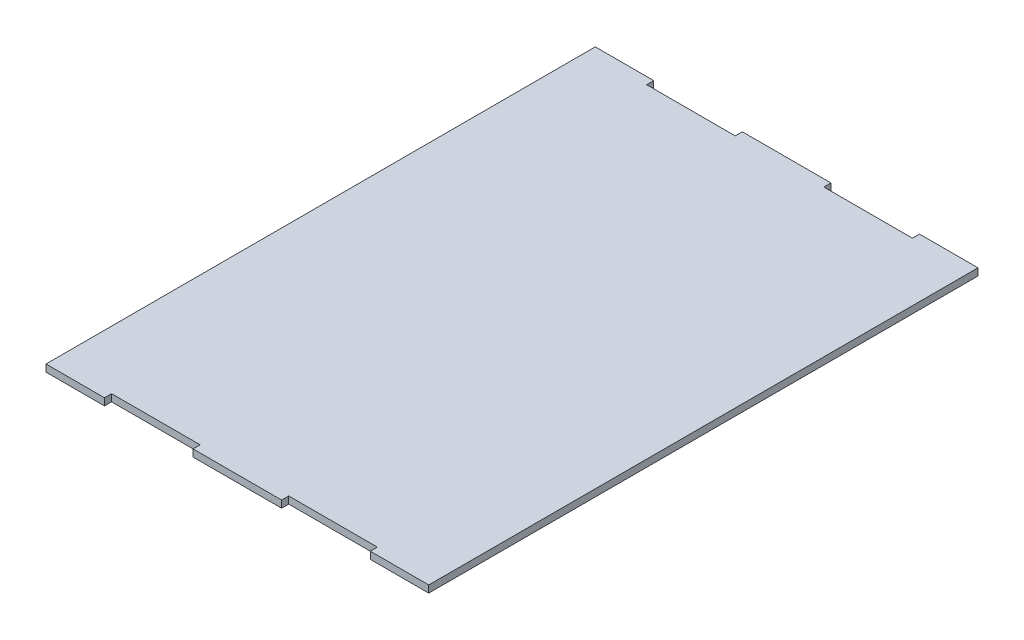
SolidWorks part; units mm, degrees
ref_plane "Alzado" through (0, 0, 0) normal (0, 0, 1) x (1, 0, 0)
ref_plane "Planta" through (0, 0, 0) normal (0, 1, 0) x (1, 0, 0)
ref_plane "Vista lateral" through (0, 0, 0) normal (1, 0, 0) x (0, 0, -1)
sketch "Croquis1" plane through (0, 0, 0) normal (0, 1, 0) x (1, 0, 0)
  line L1 (108, 155) -> (-108, 155)
  line L2 (108, 155) -> (108, -155)
  line L3 (108, -155) -> (-108, -155)
  line L4 (-108, 155) -> (-108, -155)
  line L5 (108, 155) -> (-108, -155) construction
  line L6 (108, -155) -> (-108, 155) construction
  point P0 (0, 0)
  dimension "D1" = 216
  dimension "D2" = 310
extrude "Saliente-Extruir1" add sketch "Croquis1" along normal blind 4
sketch "Croquis2" plane through (0, 4, 0) normal (0, 1, 0) x (1, 0, 0)
  line L0 (-108, -155) -> (108, -155) construction
  line L1 (-75, -155) -> (-25, -155)
  line L2 (-75, -155) -> (-75, -151)
  line L3 (-75, -151) -> (-25, -151)
  line L4 (-25, -155) -> (-25, -151)
  line L5 (-75, -155) -> (-25, -151) construction
  line L6 (-75, -151) -> (-25, -155) construction
  line L7 (108, 155) -> (-108, 155) construction
  line L8 (25, -155) -> (75, -155)
  line L9 (25, -155) -> (25, -151)
  line L10 (25, -151) -> (75, -151)
  line L11 (75, -155) -> (75, -151)
  line L12 (25, -155) -> (75, -151) construction
  line L13 (25, -151) -> (75, -155) construction
  line L14 (-75, 155) -> (-25, 155)
  line L15 (-75, 155) -> (-75, 151)
  line L16 (-75, 151) -> (-25, 151)
  line L17 (-25, 155) -> (-25, 151)
  line L18 (-75, 155) -> (-25, 151) construction
  line L19 (-75, 151) -> (-25, 155) construction
  line L21 (25, 155) -> (75, 155)
  line L22 (25, 155) -> (25, 151)
  line L23 (25, 151) -> (75, 151)
  line L24 (75, 155) -> (75, 151)
  line L25 (25, 155) -> (75, 151) construction
  line L26 (25, 151) -> (75, 155) construction
  point P4 (-50, -153)
  point P11 (50, -153)
  point P16 (-50, 153)
  point P23 (50, 153)
  dimension "D1" = 50
  dimension "D2" = 4
  dimension "D3" = 50
  dimension "D4" = 33
  dimension "D5" = 33
  dimension "D6" = 50
extrude "Cortar-Extruir1" cut sketch "Croquis2" against normal blind 4
equation "\"venesta\"= 4'grosor de la venesta"
equation "\"policarbonato\"= 4'grosor del policarbonato"
equation "\"carton_trupan\"= 3'grosor del carton trupan caso laser"
equation "\"ancho_tot\"= 310'ancho tot sin llantas"
equation "\"largo_tot\"= 400'largo tot sin camera"
equation "\"alto_estimado\"= 300'alto estimado sin lidar"
equation "\"altoparaqpaselabotella\"= 75'alto estimado para que encaje la botella"
equation "\"alturaruedaloca\"= 22"
equation "\"anchoruedaloca\"= 35"
equation "\"anchopiso1motorybaterias\"= 150"
equation "\"dist-pisorampa\"= 5"
equation "\"anchoultimopiso\"= 170"
equation "\"paredtrasera\"= 100"
equation "\"agarradorcanasta\"= 275'recolector"
equation "\"alturapiso1y2\"= 80"
equation "\"alturapiso2y3\"= 80"
equation "\"D2@Croquis1\"=\"ancho_tot\""
equation "\"D1@Saliente-Extruir1\"=\"venesta\""
equation "\"D2@Croquis2\"=\"policarbonato\""
